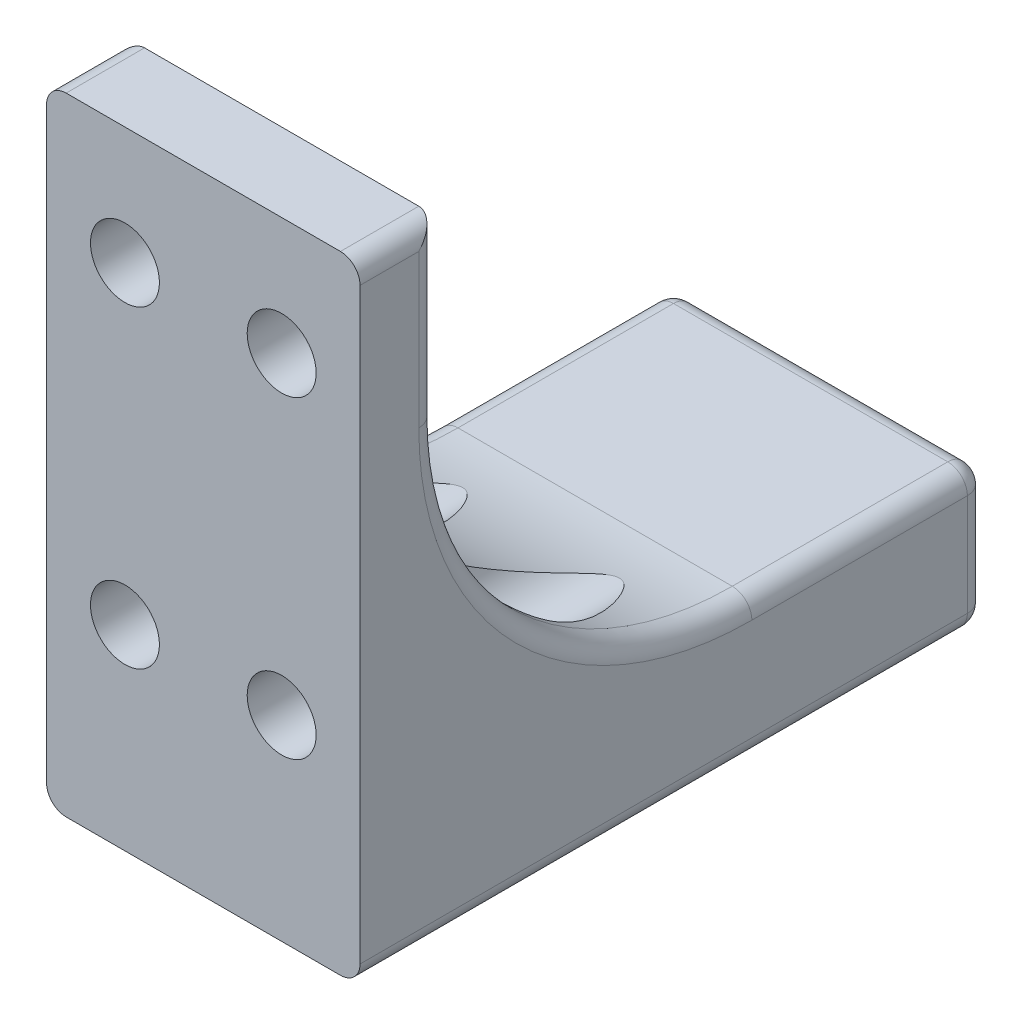
SolidWorks part; units mm, degrees
ref_plane "Front Plane" through (0, 0, 0) normal (0, 0, 1) x (1, 0, 0)
ref_plane "Top Plane" through (0, 0, 0) normal (0, 1, 0) x (1, 0, 0)
ref_plane "Right Plane" through (0, 0, 0) normal (1, 0, 0) x (0, 0, -1)
sketch "Sketch1" plane through (0, 0, 0) normal (1, 0, 0) x (0, 0, -1)
  line L0 (0, 0) -> (0, 50.8)
  line L1 (0, 50.8) -> (6.35, 50.8)
  line L2 (6.35, 50.8) -> (6.35, 11.43)
  line L3 (6.35, 11.43) -> (50.8, 11.43)
  line L4 (50.8, 11.43) -> (50.8, 0)
  line L5 (50.8, 0) -> (0, 0)
  dimension "D1" = 50.8
  dimension "D2" = 6.35
  dimension "D3" = 11.43
extrude "Boss-Extrude1" add sketch "Sketch1" along normal blind 25.4
fillet "Fillet1" radius 25.4 1 edges at (12.7, 11.43, -6.35)
sketch "Sketch2" plane through (0, 0, 0) normal (0, 0, 1) x (1, 0, 0)
  line L0 (12.7, 0) -> (12.7, 50.8) construction
  line L1 (25.4, 0) -> (0, 0) construction
  line L2 (25.4, 50.8) -> (0, 50.8) construction
  circle A0 centre (6.35, 41.275) radius 2.794
  circle A1 centre (6.35, 15.875) radius 2.794
  circle A2 centre (19.05, 41.275) radius 2.794
  circle A3 centre (19.05, 15.875) radius 2.794
  dimension "D4" = 5.588
  dimension "D1" = 6.35
  dimension "D2" = 9.525
  dimension "D3" = 25.4
extrude "Cut-Extrude1" cut sketch "Sketch2" against normal through all
sketch "Sketch3" plane through (0, 0, 0) normal (0, 0, 1) x (1, 0, 0)
  circle A0 centre (6.35, 15.875) radius 4.064
  circle A1 centre (19.05, 15.875) radius 4.064
  dimension "D1" = 8.128
extrude "Cut-Extrude2" cut sketch "Sketch3" against normal through all from offset 6.35 offset against normal yes
fillet "Fillet2" radius 1.5875 14 edges at (25.4, 43.815, -6.35) (25.4, 18.8695, -13.7895) (25.4, 0, -25.4) (12.7, 0, -50.8) (25.4, 5.715, -50.8) (0, 0, -25.4) (0, 5.715, -50.8) (25.4, 11.43, -41.275) (12.7, 11.43, -50.8) (0, 11.43, -41.275) (0, 18.8695, -13.7895) (0, 43.815, -6.35) (25.4, 50.8, -3.175) (0, 50.8, -3.175)
